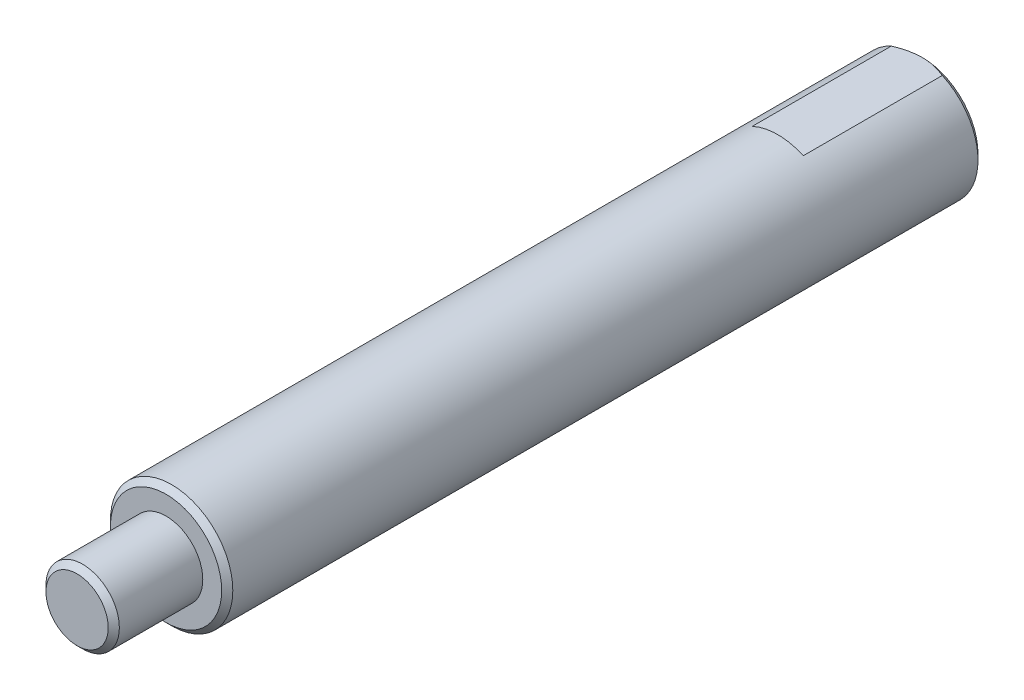
SolidWorks part; units mm, degrees
material "Q235A"
ref_plane "前视基准面" through (0, 0, 0) normal (0, 0, 1) x (1, 0, 0)
ref_plane "上视基准面" through (0, 0, 0) normal (0, 1, 0) x (1, 0, 0)
ref_plane "右视基准面" through (0, 0, 0) normal (1, 0, 0) x (0, 0, -1)
sketch "草图1" plane through (0, 0, 0) normal (0, 0, 1) x (1, 0, 0)
  circle A0 centre (0, 0) radius 5.5
  dimension "D1" = 11
extrude "拉伸1" add sketch "草图1" along normal blind 68
chamfer "倒角1" distance 0.5 angle 45 2 edges at (5.5, 0, 0) (5.5, 0, 68)
sketch "草图2" plane through (0, 0, 68) normal (0, 0, 1) x (1, 0, 0)
  circle A0 centre (0, 0) radius 3.3
  dimension "D1" = 6.6
extrude "拉伸2" add sketch "草图2" along normal blind 8
cosmetic thread "装饰螺纹线1" parameters "D2"=4.917
chamfer "倒角2" distance 0.5 angle 45 1 edges at (3.3, 0, 76)
hole_wizard "M5 螺纹孔1" positions "草图4" profile "草图3" tap size "M5" standard "GB"
sketch "草图4" plane through (0, 0, 0) normal (0, 0, -1) x (-1, 0, 0)
  point P1 (0, 0)
cosmetic thread "M5内螺纹" parameters "D1"=10, "D2"=5
sketch "草图3" plane through (0, 0, 0) normal (1, 0, 0) x (0, 1, 0)
  line L0 (0, 0) -> (0, 13.6618)
  line L1 (0, 13.6618) -> (2.1, 12.4)
  line L2 (2.1, 12.4) -> (2.1, 0)
  line L5 (2.1, 0) -> (0, 0)
  line L10 (0, 13.6618) -> (-2.1, 12.4) construction
  line L11 (0, -6.35) -> (0, 107.95) construction
  dimension "螺纹孔钻头直径" = 4.2
  dimension "螺纹孔钻头深度" = 12.4
  dimension "导头角度" = 118
chamfer "倒角3" distance 0.5 angle 45 1 edges at (-2.1, 0, 0)
sketch "草图5" plane through (0, 0, 0) normal (0, 0, 1) x (1, 0, 0)
  line L0 (0, 0) -> (0, 5) construction
  line L1 (-5, 8) -> (5, 8)
  line L2 (-5, 8) -> (-5, 5)
  line L3 (-5, 5) -> (5, 5)
  line L4 (5, 8) -> (5, 5)
  dimension "D1" = 5
  dimension "D2" = 3
  dimension "D3" = 10
extrude "拉伸3" [suppressed] cut sketch "草图5" along normal blind 13
mirror "镜向1" [suppressed] about plane through (0, 0, 0) normal (0, 1, 0)
sketch "草图6" plane through (0, 0, 0) normal (0, 0, -1) x (-1, 0, 0)
  line L0 (-2.1, 0) -> (2.1, 0) construction
  line L1 (-5, 8) -> (5, 8)
  line L2 (-5, 8) -> (-5, 5)
  line L3 (-5, 5) -> (5, 5)
  line L4 (5, 8) -> (5, 5)
  line L5 (-5, -5) -> (5, -5)
  line L6 (5, -8) -> (5, -5)
  line L7 (-5, -8) -> (5, -8)
  line L8 (-5, -8) -> (-5, -5)
  circle A0 centre (0, 0) radius 2.1 construction
  circle A1 centre (0, 0) radius 2.1 construction
  dimension "D1" = 10
  dimension "D2" = 3
  dimension "D3" = 5
  dimension "D4" = 5
extrude "切除-拉伸1" cut sketch "草图6" against normal blind 13
